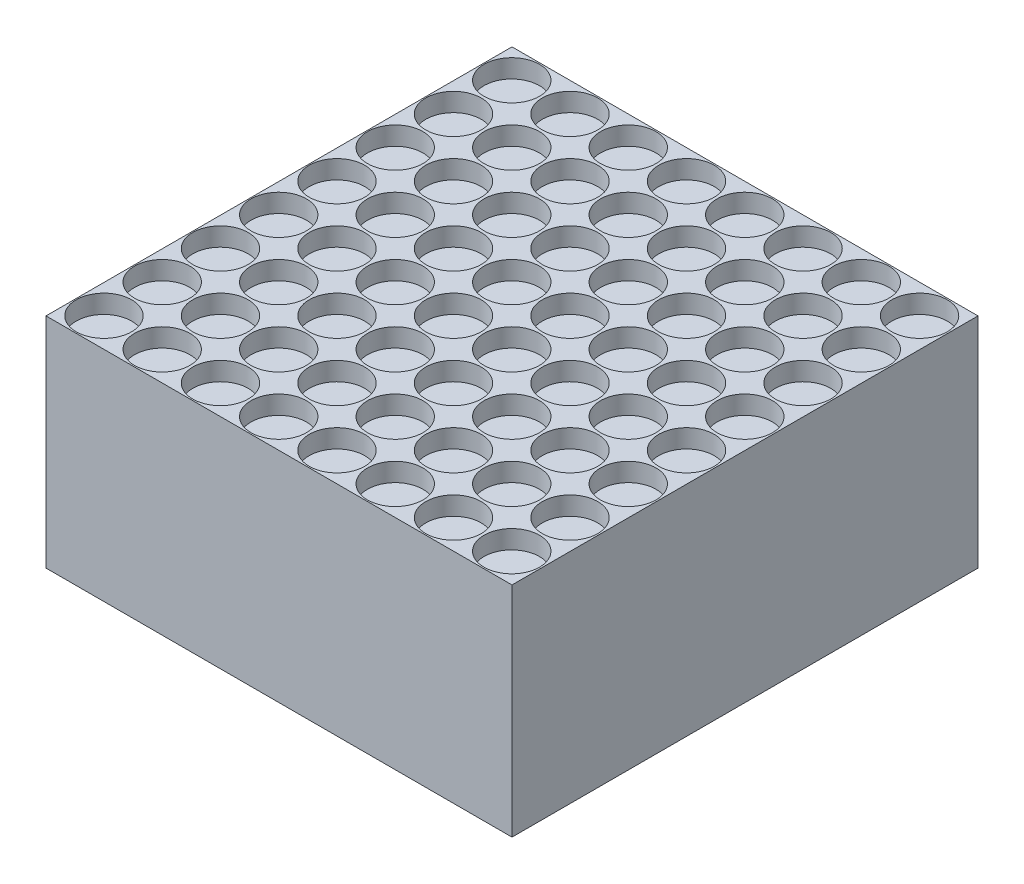
SolidWorks part; units mm, degrees
ref_plane "Front Plane" through (0, 0, 0) normal (0, 0, 1) x (1, 0, 0)
ref_plane "Top Plane" through (0, 0, 0) normal (0, 1, 0) x (1, 0, 0)
ref_plane "Right Plane" through (0, 0, 0) normal (1, 0, 0) x (0, 0, -1)
sketch "Sketch1" plane through (0, 0, 0) normal (0, 1, 0) x (1, 0, 0)
  line L1 (-12.3352, 11.7095) -> (19.6648, 11.7095)
  line L2 (-12.3352, 11.7095) -> (-12.3352, -20.2905)
  line L3 (-12.3352, -20.2905) -> (19.6648, -20.2905)
  line L4 (19.6648, 11.7095) -> (19.6648, -20.2905)
  dimension "D1" = 32
  dimension "D2" = 32
extrude "Boss-Extrude1" add sketch "Sketch1" along normal blind 15
sketch "Sketch3" plane through (0, 15, 0) normal (0, 1, 0) x (1, 0, 0)
  line L0 (-10.3532, -18.2934) -> (-6.3527, -18.2934) construction
  line L1 (-10.3532, -18.2934) -> (-10.3532, -14.2929) construction
  circle A0 centre (-10.3532, -18.2934) radius 1.905
  circle A1 centre (-6.3527, -18.2934) radius 1.905
  circle A2 centre (-2.3522, -18.2934) radius 1.905
  circle A3 centre (1.6483, -18.2934) radius 1.905
  circle A4 centre (5.6488, -18.2934) radius 1.905
  circle A5 centre (9.6493, -18.2934) radius 1.905
  circle A6 centre (13.6498, -18.2934) radius 1.905
  circle A7 centre (17.6503, -18.2934) radius 1.905
  circle A8 centre (-6.3527, -14.2929) radius 1.905
  circle A9 centre (-2.3522, -14.2929) radius 1.905
  circle A10 centre (1.6483, -14.2929) radius 1.905
  circle A11 centre (5.6488, -14.2929) radius 1.905
  circle A12 centre (9.6493, -14.2929) radius 1.905
  circle A13 centre (13.6498, -14.2929) radius 1.905
  circle A14 centre (17.6503, -14.2929) radius 1.905
  circle A15 centre (-6.3527, -10.2924) radius 1.905
  circle A16 centre (-2.3522, -10.2924) radius 1.905
  circle A17 centre (1.6483, -10.2924) radius 1.905
  circle A18 centre (5.6488, -10.2924) radius 1.905
  circle A19 centre (9.6493, -10.2924) radius 1.905
  circle A20 centre (13.6498, -10.2924) radius 1.905
  circle A21 centre (17.6503, -10.2924) radius 1.905
  circle A22 centre (-6.3527, -6.2919) radius 1.905
  circle A23 centre (-2.3522, -6.2919) radius 1.905
  circle A24 centre (1.6483, -6.2919) radius 1.905
  circle A25 centre (5.6488, -6.2919) radius 1.905
  circle A26 centre (9.6493, -6.2919) radius 1.905
  circle A27 centre (13.6498, -6.2919) radius 1.905
  circle A28 centre (17.6503, -6.2919) radius 1.905
  circle A29 centre (-6.3527, -2.2914) radius 1.905
  circle A30 centre (-2.3522, -2.2914) radius 1.905
  circle A31 centre (1.6483, -2.2914) radius 1.905
  circle A32 centre (5.6488, -2.2914) radius 1.905
  circle A33 centre (9.6493, -2.2914) radius 1.905
  circle A34 centre (13.6498, -2.2914) radius 1.905
  circle A35 centre (17.6503, -2.2914) radius 1.905
  circle A36 centre (-6.3527, 1.7091) radius 1.905
  circle A37 centre (-2.3522, 1.7091) radius 1.905
  circle A38 centre (1.6483, 1.7091) radius 1.905
  circle A39 centre (5.6488, 1.7091) radius 1.905
  circle A40 centre (9.6493, 1.7091) radius 1.905
  circle A41 centre (13.6498, 1.7091) radius 1.905
  circle A42 centre (17.6503, 1.7091) radius 1.905
  circle A43 centre (-6.3527, 5.7096) radius 1.905
  circle A44 centre (-2.3522, 5.7096) radius 1.905
  circle A45 centre (1.6483, 5.7096) radius 1.905
  circle A46 centre (5.6488, 5.7096) radius 1.905
  circle A47 centre (9.6493, 5.7096) radius 1.905
  circle A48 centre (13.6498, 5.7096) radius 1.905
  circle A49 centre (17.6503, 5.7096) radius 1.905
  circle A50 centre (-6.3527, 9.7101) radius 1.905
  circle A51 centre (-2.3522, 9.7101) radius 1.905
  circle A52 centre (1.6483, 9.7101) radius 1.905
  circle A53 centre (5.6488, 9.7101) radius 1.905
  circle A54 centre (9.6493, 9.7101) radius 1.905
  circle A55 centre (13.6498, 9.7101) radius 1.905
  circle A56 centre (17.6503, 9.7101) radius 1.905
  circle A57 centre (-10.3532, -14.2929) radius 1.905
  circle A58 centre (-10.3532, -10.2924) radius 1.905
  circle A59 centre (-10.3532, -6.2919) radius 1.905
  circle A60 centre (-10.3532, -2.2914) radius 1.905
  circle A61 centre (-10.3532, 1.7091) radius 1.905
  circle A62 centre (-10.3532, 5.7096) radius 1.905
  circle A63 centre (-10.3532, 9.7101) radius 1.905
  dimension "D1" = 3.81
  dimension "D5" = 4.0005
  dimension "D2" = 8
  dimension "D3" = 8
extrude "Cut-Extrude2" cut sketch "Sketch3" against normal blind 1.27
